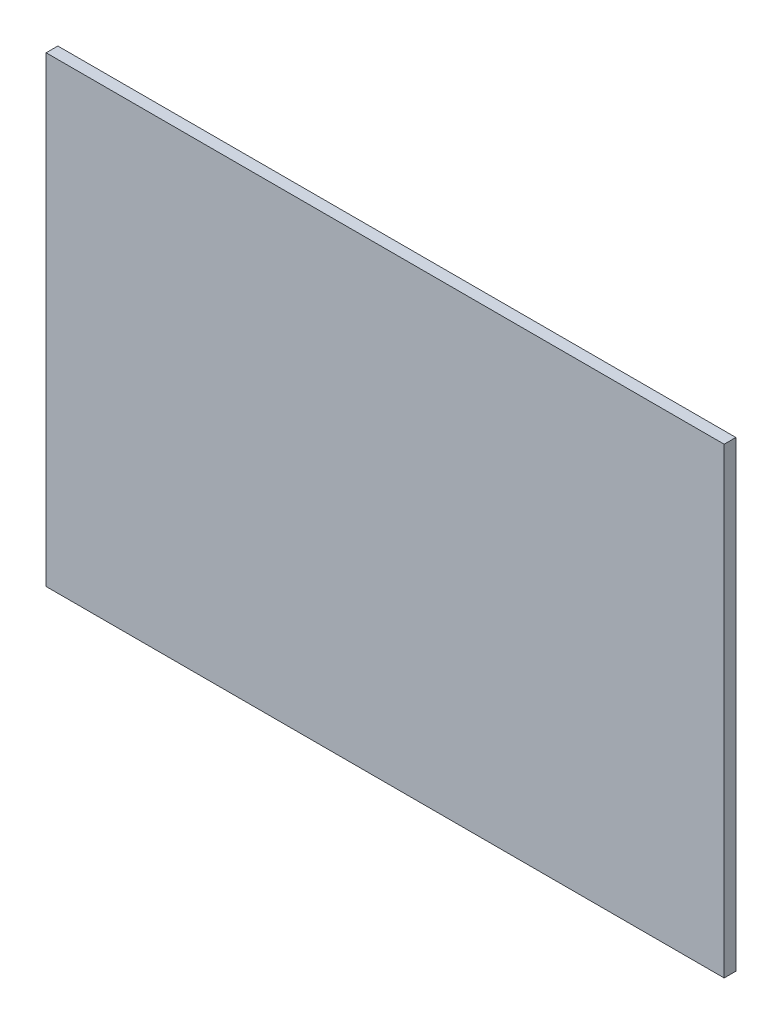
SolidWorks part; units mm, degrees
material "Thornel Mat VMA Foam Core (2)"
ref_plane "Front Plane" through (0, 0, 0) normal (0, 0, 1) x (1, 0, 0)
ref_plane "Top Plane" through (0, 0, 0) normal (0, 1, 0) x (1, 0, 0)
ref_plane "Right Plane" through (0, 0, 0) normal (1, 0, 0) x (0, 0, -1)
sketch "Sketch1" plane through (0, 0, 0) normal (0, 0, 1) x (1, 0, 0)
  line L1 (-139.7, -95.25) -> (139.7, -95.25)
  line L2 (-139.7, -95.25) -> (-139.7, 95.25)
  line L3 (-139.7, 95.25) -> (139.7, 95.25)
  line L4 (139.7, -95.25) -> (139.7, 95.25)
  line L5 (-139.7, -95.25) -> (139.7, 95.25) construction
  line L6 (-139.7, 95.25) -> (139.7, -95.25) construction
  point P0 (0, 0)
  dimension "D1" = 190.5
  dimension "D2" = 279.4
extrude "Boss-Extrude1" add sketch "Sketch1" along normal blind 4.826
